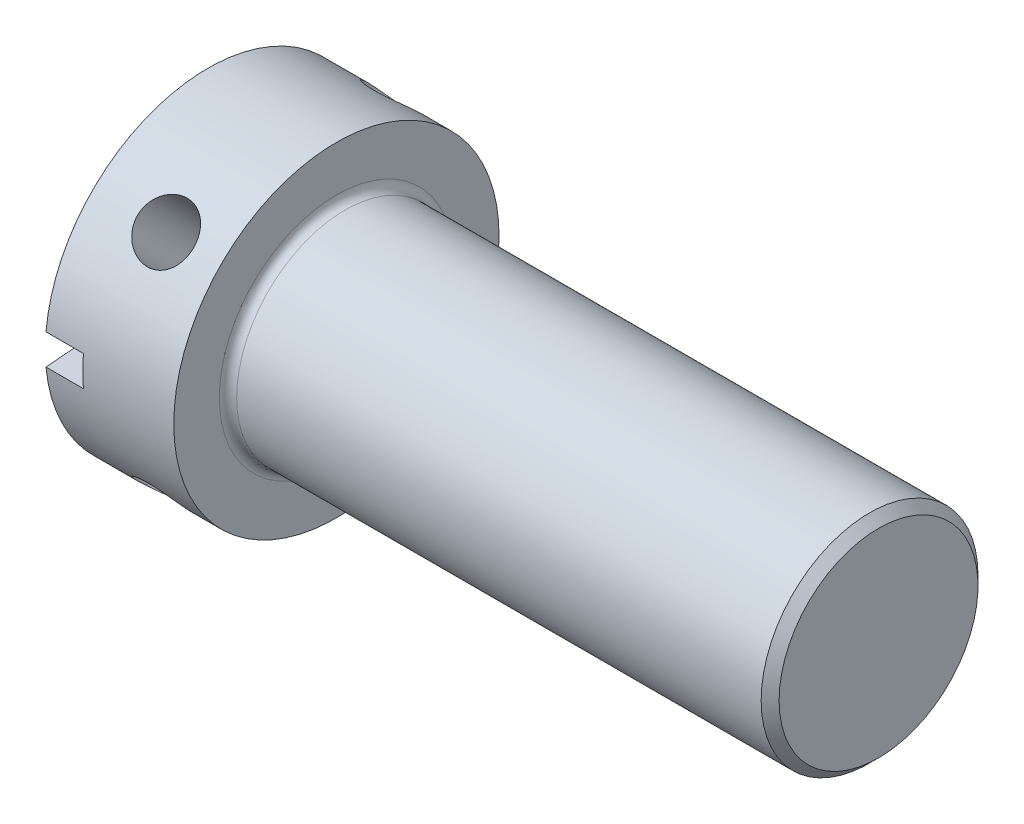
SolidWorks part; units mm, degrees
ref_plane "Plane1" through (0, 0, 0) normal (0, 0, 1) x (1, 0, 0)
ref_plane "Plane2" through (0, 0, 0) normal (0, 1, 0) x (1, 0, 0)
ref_plane "Plane3" through (0, 0, 0) normal (1, 0, 0) x (0, 0, -1)
sketch "BodySke" plane through (0, 0, 0) normal (0, 0, 1) x (1, 0, 0)
  line L1 (0.65, 15) -> (12.5, 15)
  line L2 (12.5, 15) -> (12.5, 10)
  line L3 (12.5, 10) -> (61.672, 10)
  line L4 (62.5, 9.172) -> (62.5, 0)
  line L5 (62.5, 0) -> (0, 0)
  line L6 (-31.75, 0) -> (127, 0) construction
  line L7 (0.65, 15) -> (0.65, -2.9344) construction
  line L8 (62.5, 9.172) -> (61.672, 10)
  line L10 (62.5, -9.172) -> (61.672, -10) construction
  line L11 (14, 4.525) -> (14, -1.825) construction
  line L12 (22.5, 4.525) -> (22.5, -1.825) construction
  line L13 (2.5, 4.525) -> (2.5, -1.825) construction
  arc A0 (0, 0) -> (0.65, 15) centre (173.4019, 0) cw
  dimension "Length" = 50
  dimension "Body_ch_ang" = 45
  dimension "Diameter" = 20
  dimension "Minor_dia" = 18.344
  dimension "Advance" = 1.5
  dimension "Thread_nom" = 40
  dimension "Thread_length" = 60
  dimension "Head_dia" = 30
  dimension "Head_ht" = 12.5
  dimension "Curve" = 0.65
revolve "Base-Revolve" add sketch "BodySke"
cosmetic thread "ThreadCosmetic" [suppressed]
fillet "Fillet1" radius 0.8 1 edges at (12.5, 0, 10)
sketch "ThdSchSke" plane through (0, 0, 0) normal (0, 0, 1) x (1, 0, 0)
  line L0 (22.5, -9.172) -> (21.9202, -10)
  line L1 (22.5, -9.172) -> (23.0798, -10)
  line L2 (23.0798, -10) -> (23.0798, -12.5)
  line L3 (-3.175, 0) -> (5.1513, 0) construction
  line L5 (23.0798, -12.5) -> (21.9202, -12.5)
  line L6 (21.9202, -12.5) -> (21.9202, -10)
  dimension "Thread_minor" = 18.344
  dimension "Diameter" = 20
  dimension "SideAngle" = 55
  dimension "VeeAngle" = 70
  dimension "Overcut" = 25
  dimension "Start" = 22.5
revolve "ThreadSchematic" [suppressed] cut sketch "ThdSchSke" angle 360 about L3
pattern_linear "ThdSchPat" [suppressed]
sketch "Sketch3" plane through (0, 0, 0) normal (0, 0, 1) x (1, 0, 0)
  line L0 (-8.4745, 0) -> (15.3992, 0) construction
  line L1 (-31.75, 0) -> (127, 0) construction
  line L2 (0.0057, 1.405) -> (4.1057, 1.405)
  line L3 (0.0057, -1.405) -> (4.1057, -1.405)
  line L4 (4.1057, 1.405) -> (4.1057, -1.405)
  arc A0 (0.65, 15) -> (0.65, -15) centre (173.4019, 0) ccw construction
  point P12 (4.1057, 0)
  dimension "Slot_wid" = 2.81
  dimension "Slot_dep" = 4.1
extrude "Slot" cut sketch "Sketch3" against normal through all and the other way through all
ref_plane "Plane4" through (0, 0, 0) normal (0, 0.7071, 0.7071) x (1, 0, 0)
sketch "HoleSke" plane through (0, 0, 0) normal (0, 0.7071, 0.7071) x (1, 0, 0)
  line L0 (12.5, -15) -> (12.5, 15) construction
  circle A0 centre (7.35, 0) radius 2.59
  dimension "diameter" = 5.18
  dimension "position" = 5.15
extrude "Drill Hole" cut sketch "HoleSke" against normal through all and the other way through all
pattern_circular "Drill Holes" count 2 every 90 about axis through (0, 0, 0) along (1, 0, 0) of "Drill Hole"
equation "\"Thread_minor@ThreadCosmetic\"  =  \"Minor_dia@BodySke\""
equation "\"Thread_length@ThreadCosmetic\" = ((sgn( (\"Length@BodySke\" - \"Advance@BodySke\" * 3.0) - \"Thread_nom@BodySke\" )-1)*( (\"Length@BodySke\" - \"Advance@BodySke\" * 3.0) - \"Thread_nom@BodySke\" ))/-2+ \"Thread_nom@BodySke\""
equation "\"Thread_minor@ThdSchSke\" = \"Minor_dia@BodySke\""
equation "\"Diameter@ThdSchSke\" = \"Diameter@BodySke\""
equation "\"Overcut@ThdSchSke\" = \"Diameter@BodySke\" * 1.25"
equation "\"Start@ThdSchSke\" = \"Head_ht@BodySke\" + \"Length@BodySke\" - \"Thread_length@ThreadCosmetic\"  '---Non-countersunk---"
equation "\"Num_threads@ThdSchPat\" = int( \"Thread_length@ThreadCosmetic\" / \"Advance@BodySke\" + 0.999 )  + 1"
equation "\"Advance@ThdSchPat\" = \"Thread_length@ThreadCosmetic\" /  (\"Num_threads@ThdSchPat\" - 1) 'relax it"
equation "\"Num_threads@ThdSchPat\" = \"Num_threads@ThdSchPat\" - sgn( \"Num_threads@ThdSchPat\" - 1) '---chamfered tips only---"
